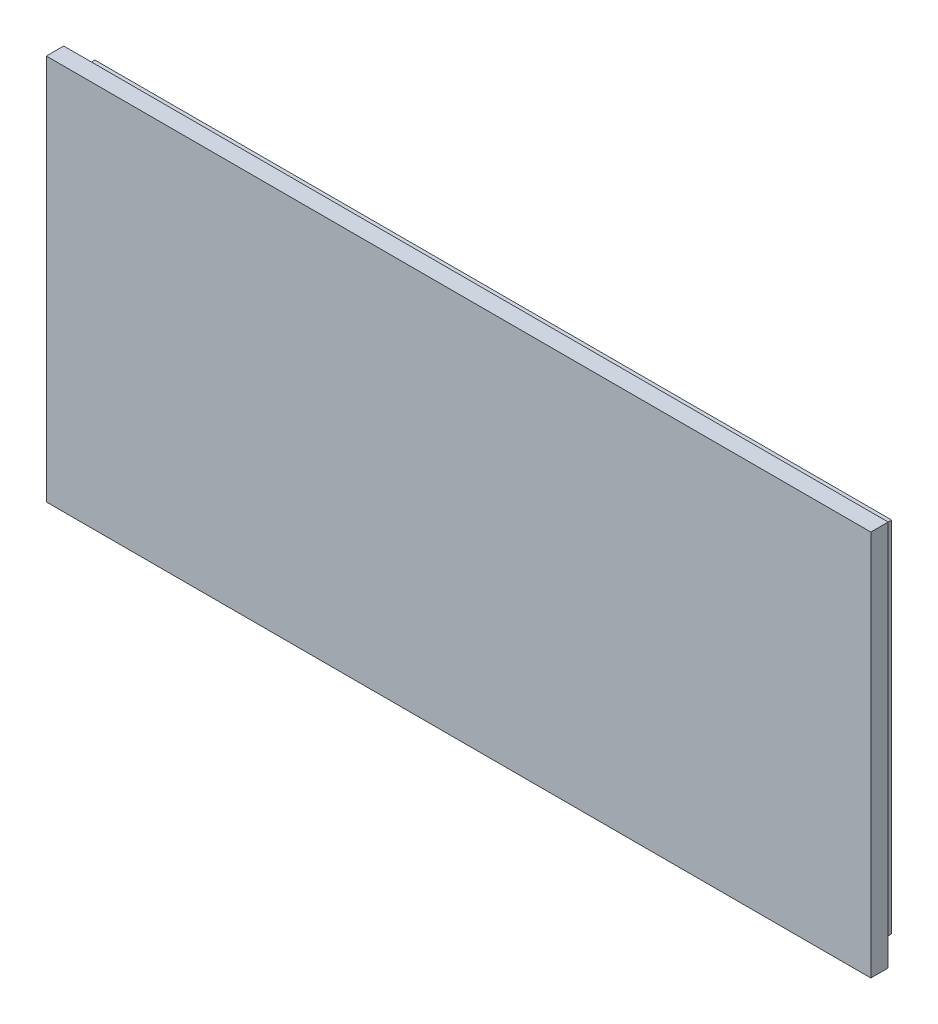
SolidWorks part; units mm, degrees
ref_plane "Front Plane" through (0, 0, 0) normal (0, 0, 1) x (1, 0, 0)
ref_plane "Top Plane" through (0, 0, 0) normal (0, 1, 0) x (1, 0, 0)
ref_plane "Right Plane" through (0, 0, 0) normal (1, 0, 0) x (0, 0, -1)
sketch "Sketch1" plane through (0, 0, 0) normal (0, 0, 1) x (1, 0, 0)
  line L1 (-115.5, 48) -> (74.5, 48)
  line L2 (-115.5, 48) -> (-115.5, -41)
  line L3 (-115.5, -41) -> (74.5, -41)
  line L4 (74.5, 48) -> (74.5, -41)
extrude "Boss-Extrude1" add sketch "Sketch1" along normal blind 4
sketch "Sketch2" plane through (0, 0, 0) normal (0, 0, -1) x (-1, 0, 0)
  line L4 (110.3, -35.8) -> (110.3, 42.8)
  line L5 (110.3, 42.8) -> (-69.3, 42.8)
  line L6 (-69.3, 42.8) -> (-69.3, -35.8)
  line L7 (-69.3, -35.8) -> (110.3, -35.8)
  line L8 (112.3, 44.8) -> (-71.3, 44.8)
  line L9 (-71.3, 44.8) -> (-71.3, -37.8)
  line L10 (-71.3, -37.8) -> (112.3, -37.8)
  line L11 (112.3, -37.8) -> (112.3, 44.8)
  line L12 (112.3, 44.8) -> (-71.3, 44.8)
  line L13 (-71.3, 44.8) -> (-71.3, -37.8)
  line L14 (-71.3, -37.8) -> (112.3, -37.8)
  line L15 (112.3, -37.8) -> (112.3, 44.8)
  dimension "D1" = 3.2
  dimension "D2" = 2
extrude "Boss-Extrude2" add sketch "Sketch2" along normal blind 4
sketch "Sketch3" plane through (0, -37.8, 0) normal (0, -1, 0) x (1, 0, 0)
  line L0 (-115.5, 0) -> (74.5, 0) construction
  line L1 (-102.3, 0) -> (-92.3, 0)
  line L2 (-102.3, 0) -> (-102.3, -10)
  line L3 (-102.3, -10) -> (-92.3, -10)
  line L4 (-92.3, 0) -> (-92.3, -10)
  line L5 (-112.3, -4) -> (-112.3, 0) construction
  dimension "D1" = 10
  dimension "D2" = 10
  dimension "D3" = 10
